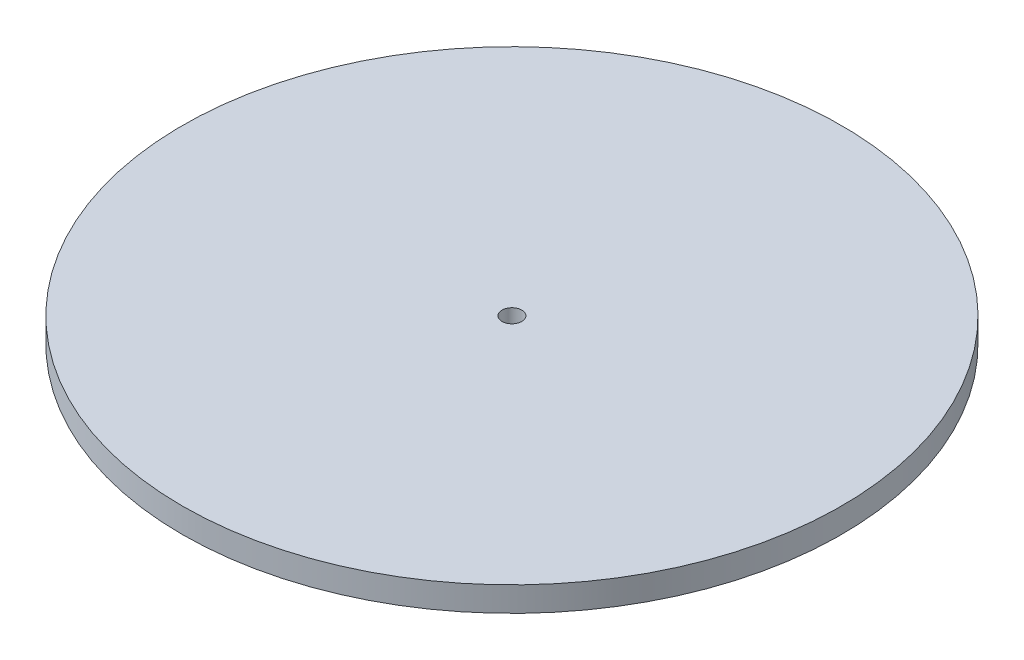
SolidWorks part; units mm, degrees
ref_plane "Front Plane" through (0, 0, 0) normal (0, 0, 1) x (1, 0, 0)
ref_plane "Top Plane" through (0, 0, 0) normal (0, 1, 0) x (1, 0, 0)
ref_plane "Right Plane" through (0, 0, 0) normal (1, 0, 0) x (0, 0, -1)
sketch "Sketch3" plane through (0, 0, 0) normal (0, 0, 1) x (1, 0, 0)
  line L0 (37, 16.8887) -> (37, 20.8887) construction
  line L1 (37, 20.8887) -> (0, 20.8887) construction
  line L2 (0, 20.8887) -> (0, 0) construction
  line L4 (1.2, 20.8887) -> (1.2, 15.8887)
  line L5 (1.2, 15.8887) -> (0, 15.8887)
  line L6 (0, 15.8887) -> (0, 0)
  line L7 (37, 16.8887) -> (40, 16.8887) construction
  line L8 (40, 16.8887) -> (40, 20.8887) construction
  line L9 (40, 20.8887) -> (1.2, 20.8887)
  line L10 (37, 16.8887) -> (37, 17.8887)
  line L11 (37, 17.8887) -> (40, 17.8887)
  line L12 (40, 17.8887) -> (40, 20.8887)
  spline S0 degree 8 poles (-3.6915, 0.9734) (1.8574, -2.1452) (7.4063, 1.4516) (12.9551, 5.0728) (18.504, 6.9377) (24.0529, 11.047) (29.6018, 13.0034) (35.1506, 16.2022) (40.6995, 18.585) knots 0 0 0 0 0 0 0 0 0 1 1 1 1 1 1 1 1 1 construction
  spline S1 degree 8 poles (0, 0) (4.625, -0.0684) (9.25, 2.5633) (13.875, 5.1937) (18.5, 7.3776) (23.125, 10.1213) (27.75, 12.3188) (32.375, 14.6807) (37, 16.8887) knots 0.083158 0.083158 0.083158 0.083158 0.083158 0.083158 0.083158 0.083158 0.083158 0.916661 0.916661 0.916661 0.916661 0.916661 0.916661 0.916661 0.916661 0.916661
  dimension "D1" = 3
  dimension "D2" = 1.2
  dimension "D3" = 5
  dimension "D4" = 3
  dimension "D5" = 40
  dimension "D6" = 16.8887
  dimension "D7" = 37
  dimension "D8" = 4
revolve "Revolve4" add sketch "Sketch3" angle 360 about L2
sketch "Sketch5" plane through (0, 20.8887, 0) normal (0, 1, 0) x (1, 0, 0)
  circle A0 centre (0, 0) radius 1.2
  circle A2 centre (0, 0) radius 1.2 construction
extrude "Cut-Extrude1" cut sketch "Sketch5" against normal through all
